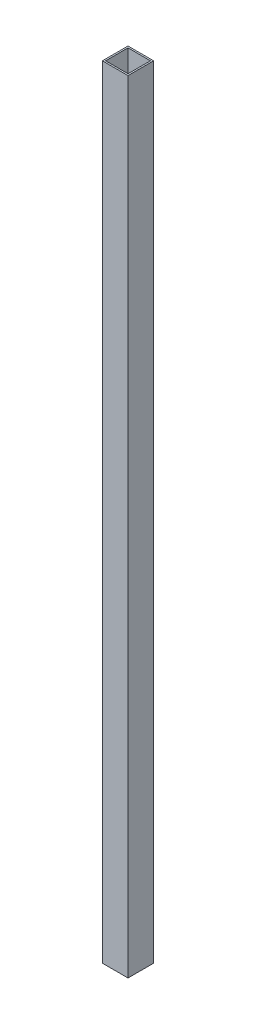
SolidWorks part; units mm, degrees
ref_plane "Front Plane" through (0, 0, 0) normal (0, 0, 1) x (1, 0, 0)
ref_plane "Top Plane" through (0, 0, 0) normal (0, 1, 0) x (1, 0, 0)
ref_plane "Right Plane" through (0, 0, 0) normal (1, 0, 0) x (0, 0, -1)
sketch "Sketch1" plane through (0, 0, 0) normal (0, 1, 0) x (1, 0, 0)
  line L1 (12.7, 12.7) -> (-12.7, 12.7)
  line L2 (12.7, 12.7) -> (12.7, -12.7)
  line L3 (12.7, -12.7) -> (-12.7, -12.7)
  line L4 (-12.7, 12.7) -> (-12.7, -12.7)
  line L5 (12.7, 12.7) -> (-12.7, -12.7) construction
  line L6 (12.7, -12.7) -> (-12.7, 12.7) construction
  line L7 (11.1125, 11.1125) -> (-11.1125, 11.1125)
  line L8 (11.1125, 11.1125) -> (11.1125, -11.1125)
  line L9 (11.1125, -11.1125) -> (-11.1125, -11.1125)
  line L10 (-11.1125, 11.1125) -> (-11.1125, -11.1125)
  line L11 (11.1125, 11.1125) -> (-11.1125, -11.1125) construction
  line L12 (11.1125, -11.1125) -> (-11.1125, 11.1125) construction
  point P1 (0, 0)
  point P6 (0, 0)
  dimension "D1" = 25.4
  dimension "D2" = 25.4
  dimension "D3" = 1.5875
  dimension "D4" = 1.5875
extrude "Boss-Extrude1" add sketch "Sketch1" along normal blind 774.7
